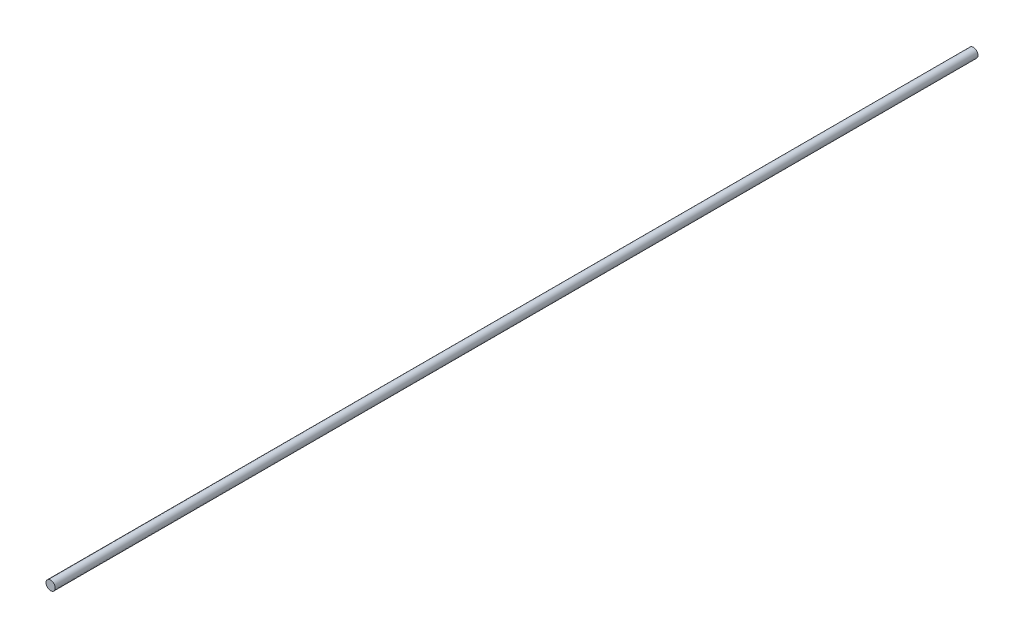
SolidWorks part; units mm, degrees
material "Hexcel AS4C (3000 Filaments)"
ref_plane "Front Plane" through (0, 0, 0) normal (0, 0, 1) x (1, 0, 0)
ref_plane "Top Plane" through (0, 0, 0) normal (0, 1, 0) x (1, 0, 0)
ref_plane "Right Plane" through (0, 0, 0) normal (1, 0, 0) x (0, 0, -1)
sketch "Sketch1" plane through (0, 0, 0) normal (0, 0, 1) x (1, 0, 0)
  circle A0 centre (0, 0) radius 1.5
  dimension "D1" = 3
extrude "Boss-Extrude1" add sketch "Sketch1" along normal blind 300
